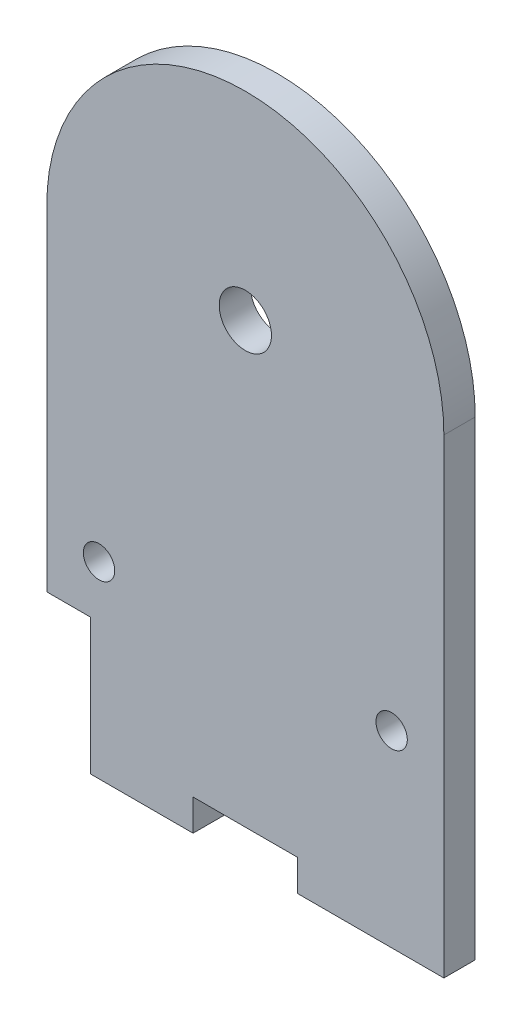
SolidWorks part; units mm, degrees
material "Acrylic (Medium-high impact)"
ref_plane "Front Plane" through (0, 0, 0) normal (0, 0, 1) x (1, 0, 0)
ref_plane "Top Plane" through (0, 0, 0) normal (0, 1, 0) x (1, 0, 0)
ref_plane "Right Plane" through (0, 0, 0) normal (1, 0, 0) x (0, 0, -1)
sketch "Sketch1" plane through (0, 0, 0) normal (0, 0, 1) x (1, 0, 0)
  line L0 (-19, 0) -> (-19, -32)
  line L1 (-14.8, -45) -> (-5, -45)
  line L2 (19, -45) -> (19, 0)
  line L3 (0, 0) -> (0, -42) construction
  line L4 (5, -42) -> (-5, -42)
  line L5 (-5, -42) -> (-5, -45)
  line L6 (5, -42) -> (5, -45)
  line L7 (5, -45) -> (19, -45)
  line L8 (-19, -32) -> (-14.8, -32)
  line L9 (-14.8, -32) -> (-14.8, -45)
  arc A0 (19, 0) -> (-19, 0) centre (0, 0) ccw
  circle A1 centre (0, 0) radius 2.5
  arc A2 (-19, 0) -> (19, 0) centre (0, 0) ccw construction
  circle A3 centre (-14, -27) radius 1.5
  circle A6 centre (14, -27) radius 1.5
  dimension "D3" = 38
  dimension "D4" = 18
  dimension "D2" = 45
  dimension "D8" = 5
  dimension "D1" = 3
  dimension "D5" = 5
  dimension "D6" = 5
  dimension "D9" = 3
  dimension "D10" = 10
  dimension "D11" = 4.2
  dimension "D12" = 13
extrude "Boss-Extrude1" add sketch "Sketch1" along normal blind 3
